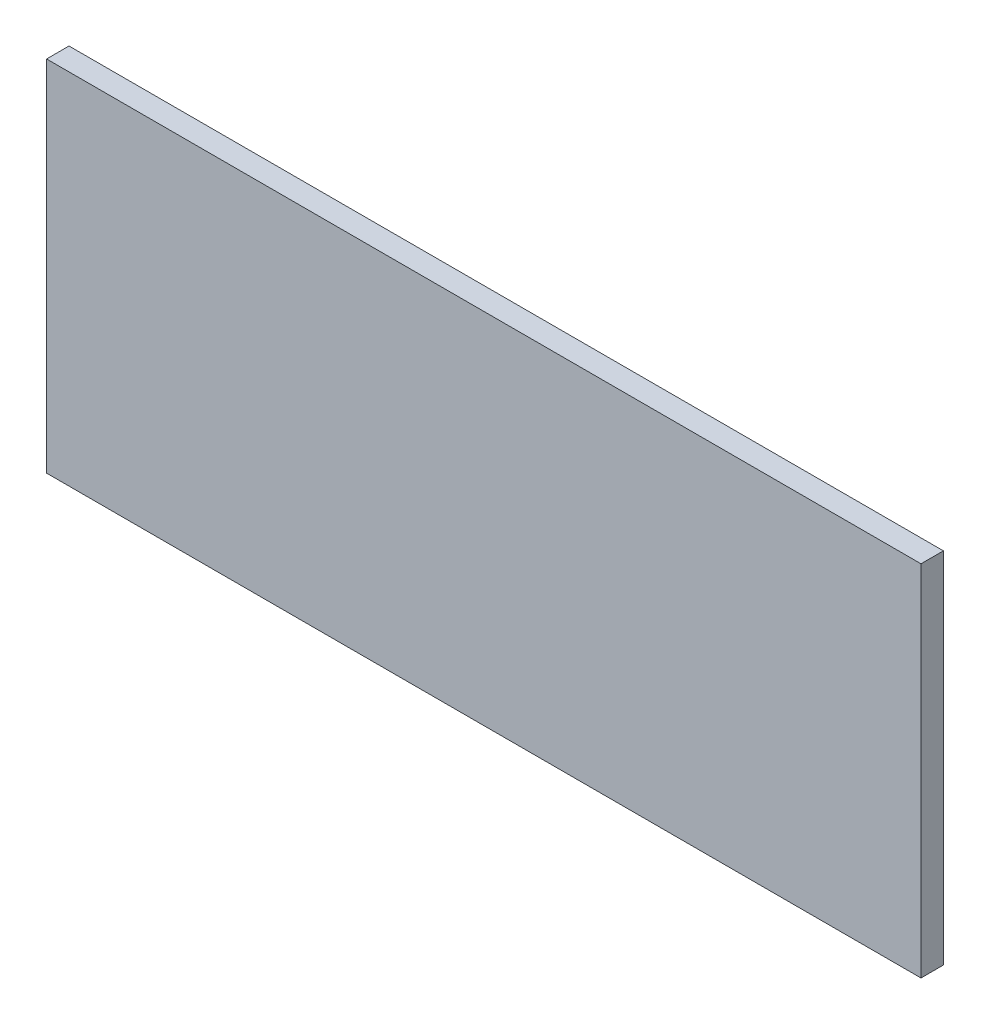
SolidWorks part; units mm, degrees
ref_plane "Piano frontale" through (0, 0, 0) normal (0, 0, 1) x (1, 0, 0)
ref_plane "Piano superiore" through (0, 0, 0) normal (0, 1, 0) x (1, 0, 0)
ref_plane "Piano destro" through (0, 0, 0) normal (1, 0, 0) x (0, 0, -1)
sketch "Schizzo1" plane through (0, 0, 0) normal (0, 0, 1) x (1, 0, 0)
  line L1 (-19.5, -8) -> (19.5, -8)
  line L2 (-19.5, -8) -> (-19.5, 8)
  line L3 (-19.5, 8) -> (19.5, 8)
  line L4 (19.5, -8) -> (19.5, 8)
  line L5 (-19.5, -8) -> (19.5, 8) construction
  line L6 (-19.5, 8) -> (19.5, -8) construction
  point P0 (0, 0)
  dimension "D1" = 16
  dimension "D2" = 39
extrude "Estrusione-Estrusione1" add sketch "Schizzo1" along normal blind 1
